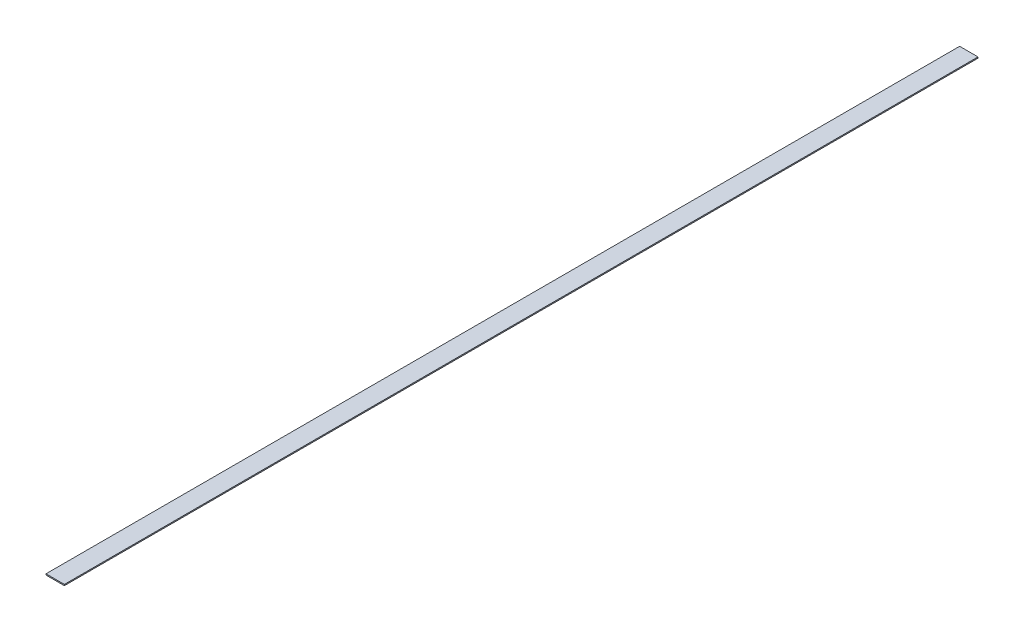
SolidWorks part; units mm, degrees
ref_plane "Front Plane" through (0, 0, 0) normal (0, 0, 1) x (1, 0, 0)
ref_plane "Top Plane" through (0, 0, 0) normal (0, 1, 0) x (1, 0, 0)
ref_plane "Right Plane" through (0, 0, 0) normal (1, 0, 0) x (0, 0, -1)
sketch "Sketch1" plane through (0, 0, 0) normal (0, 1, 0) x (1, 0, 0)
  line L1 (0, 0) -> (50.8, 0)
  line L2 (0, 0) -> (0, 2526.03)
  line L3 (0, 2526.03) -> (50.8, 2526.03)
  line L4 (50.8, 0) -> (50.8, 2526.03)
  line L5 (0, 0) -> (50.8, 0) construction
  dimension "D1" = 50.8
  dimension "D2" = 2526.03
extrude "Boss-Extrude1" add sketch "Sketch1" along normal blind 3.175
